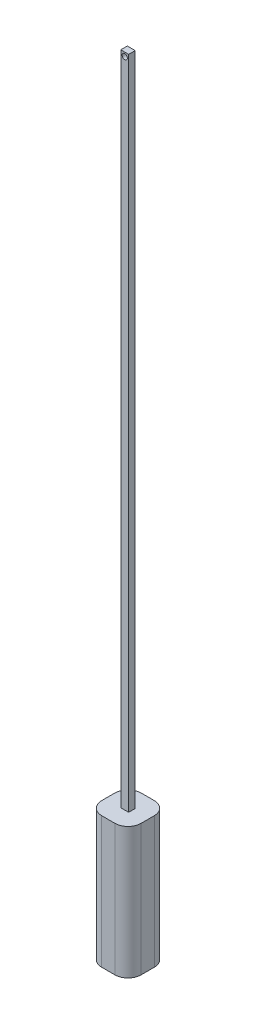
SolidWorks part; units mm, degrees
material "Malleable Cast Iron"
ref_plane "Front Plane" through (0, 0, 0) normal (0, 0, 1) x (1, 0, 0)
ref_plane "Top Plane" through (0, 0, 0) normal (0, 1, 0) x (1, 0, 0)
ref_plane "Right Plane" through (0, 0, 0) normal (1, 0, 0) x (0, 0, -1)
sketch "Sketch1" plane through (0, 0, 0) normal (0, 0, 1) x (1, 0, 0)
  line L1 (-3, 3) -> (3, 3)
  line L2 (-3, 3) -> (-3, -497)
  line L3 (-3, -497) -> (3, -497)
  line L4 (3, 3) -> (3, -497)
  circle A0 centre (0, 0) radius 2
  dimension "D1" = 4
  dimension "D2" = 3
  dimension "D3" = 6
  dimension "D4" = 3
  dimension "D5" = 500
extrude "Boss-Extrude1" add sketch "Sketch1" along normal blind 5
sketch "Sketch2" plane through (0, -497, 0) normal (0, -1, 0) x (1, 0, 0)
  line L0 (3, 5) -> (3, 0) construction
  line L1 (-15, 17.5) -> (15, 17.5)
  line L2 (-15, 17.5) -> (-15, -12.5)
  line L3 (-15, -12.5) -> (15, -12.5)
  line L4 (15, 17.5) -> (15, -12.5)
  line L5 (-15, 17.5) -> (15, -12.5) construction
  line L6 (-15, -12.5) -> (15, 17.5) construction
  line L8 (-3, 0) -> (3, 0) construction
  point P0 (0, 2.5)
  dimension "D1" = 30
  dimension "D2" = 30
  dimension "D3" = 3
  dimension "D4" = 2.5
extrude "Boss-Extrude2" add sketch "Sketch2" along normal blind 100
fillet "Fillet1" radius 10 4 edges at (-15, -547, -12.5) (15, -547, -12.5) (15, -547, 17.5) (-15, -547, 17.5)
